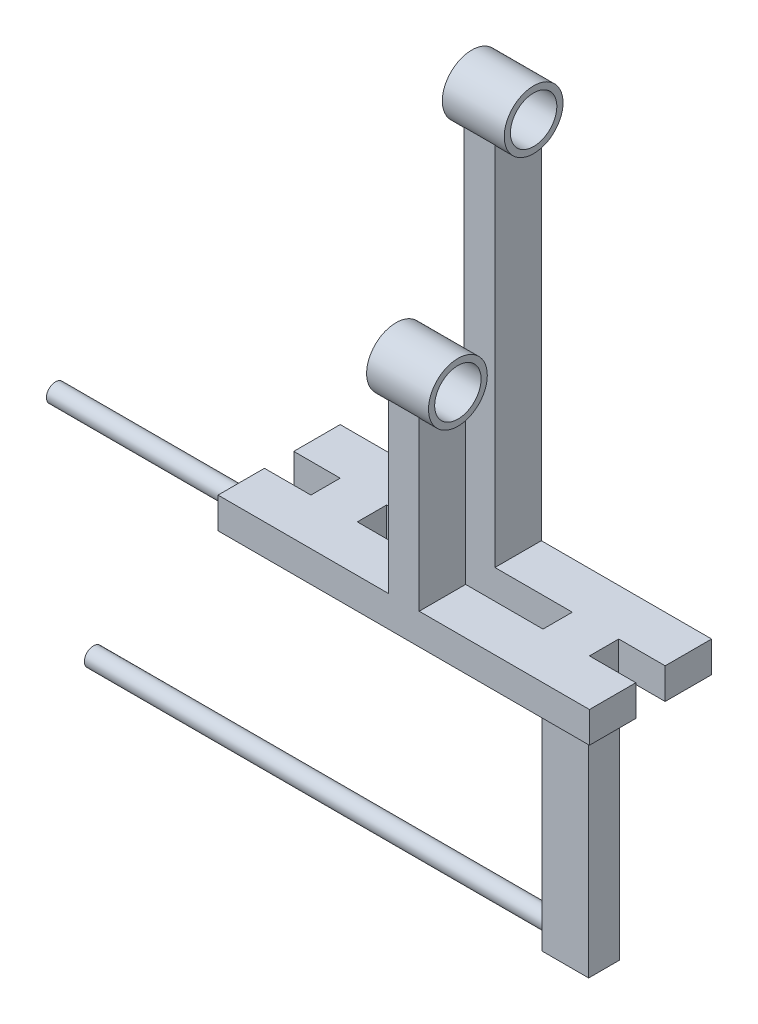
SolidWorks part; units mm, degrees
ref_plane "Front Plane" through (0, 0, 0) normal (0, 0, 1) x (1, 0, 0)
ref_plane "Top Plane" through (0, 0, 0) normal (0, 1, 0) x (1, 0, 0)
ref_plane "Right Plane" through (0, 0, 0) normal (1, 0, 0) x (0, 0, -1)
sketch "Sketch2" plane through (0, 0, 0) normal (0, 1, 0) x (1, 0, 0)
  line L33 (60, -15) -> (-60, -15)
  line L34 (-60, -15) -> (-60, 0)
  line L46 (-60, 0) -> (-45, 0)
  line L47 (-45, 0) -> (-45, 9.4666)
  line L48 (-45, 9.4666) -> (-60, 9.4666)
  line L49 (-60, 9.4666) -> (-60, 24.4666)
  line L50 (-60, 24.4666) -> (60, 24.4666)
  line L51 (60, 24.4666) -> (60, 9.4666)
  line L52 (60, 9.4666) -> (45, 9.4666)
  line L53 (45, 9.4666) -> (45, 0)
  line L54 (45, 0) -> (60, 0)
  line L55 (60, 0) -> (60, -15)
  line L57 (-30, 0) -> (30, 0)
  line L58 (-30, 0) -> (-30, 9.4666)
  line L59 (-30, 9.4666) -> (30, 9.4666)
  line L60 (30, 0) -> (30, 9.4666)
  point P21 (0, 0)
  dimension "D1" = 120
  dimension "D2" = 39.4666
  dimension "D3" = 15
  dimension "D4" = 60
  dimension "D5" = 15
  dimension "D6" = 15
extrude "Boss-Extrude2" add sketch "Sketch2" along normal blind 10
sketch "Sketch3" plane through (0, 10, 0) normal (0, 1, 0) x (1, 0, 0)
  line L0 (-30, 0) -> (30, 0) construction
  line L1 (-5, 0) -> (5, 0)
  line L2 (-5, 0) -> (-5, -15)
  line L3 (-5, -15) -> (5, -15)
  line L4 (5, 0) -> (5, -15)
  line L5 (-60, -15) -> (60, -15) construction
  line L6 (60, 24.4666) -> (-60, 24.4666) construction
  line L7 (-5, 24.4666) -> (5, 24.4666)
  line L8 (-5, 24.4666) -> (-5, 9.4666)
  line L9 (-5, 9.4666) -> (5, 9.4666)
  line L10 (5, 24.4666) -> (5, 9.4666)
  line L11 (30, 9.4666) -> (-30, 9.4666) construction
  dimension "D1" = 5
  dimension "D2" = 10
extrude "Boss-Extrude3" add sketch "Sketch3" along normal blind 60
sketch "Sketch4" plane through (0, 70, 0) normal (0, 1, 0) x (1, 0, 0)
  line L4 (-5, 24.4666) -> (-5, 9.4666)
  line L5 (-5, 9.4666) -> (5, 9.4666)
  line L6 (5, 9.4666) -> (5, 24.4666)
  line L7 (5, 24.4666) -> (-5, 24.4666)
  line L8 (-5, 24.4666) -> (-5, 9.4666)
  line L9 (-5, 9.4666) -> (5, 9.4666)
  line L10 (5, 9.4666) -> (5, 24.4666)
  line L11 (5, 24.4666) -> (-5, 24.4666)
  dimension "D1" = 0
extrude "Boss-Extrude4" add sketch "Sketch4" along normal blind 64.0503
sketch "Sketch6" plane through (0, 0, 0) normal (1, 0, 0) x (0, 0, -1)
  line L0 (-15, 70) -> (0, 70) construction
  line L1 (9.4666, 134.0503) -> (24.4666, 134.0503) construction
  line L2 (0, 70) -> (0, 10) construction
  line L3 (24.4666, 134.0503) -> (24.4666, 10) construction
  circle A0 centre (-7.5, 70) radius 7.5
  circle A1 centre (16.9666, 134.0503) radius 7.5
  dimension "D1" = 15
  dimension "D2" = 7.5
  dimension "D3" = 7.5
extrude "Extrude-Thin1" add sketch "Sketch6" along normal mid plane 20 thin
sketch "Sketch7" plane through (5, 0, 0) normal (1, 0, 0) x (0, 0, -1)
  line L1 (0, 70) -> (-15, 70)
  line L2 (0, 70) -> (-15, 70)
  line L3 (24.4666, 134.0503) -> (9.4666, 134.0503)
  line L4 (24.4666, 134.0503) -> (9.4666, 134.0503)
  arc A1 (-15, 70) -> (0, 70) centre (-7.5, 70) ccw
  arc A2 (-15, 70) -> (0, 70) centre (-7.5, 70) ccw
  arc A3 (9.4666, 134.0503) -> (24.4666, 134.0503) centre (16.9666, 134.0503) ccw
  arc A4 (9.4666, 134.0503) -> (24.4666, 134.0503) centre (16.9666, 134.0503) ccw
  dimension "D1" = 0
  dimension "D2" = 0
extrude "Cut-Extrude1" cut sketch "Sketch7" against normal through all both and the other way through all
sketch "Sketch8" plane through (0, 0, 0) normal (0, -1, 0) x (1, 0, 0)
  line L0 (30, 0) -> (30, -9.4666) construction
  line L1 (30, -9.75) -> (45, -9.75)
  line L2 (30, -9.75) -> (30, 0.25)
  line L3 (30, 0.25) -> (45, 0.25)
  line L4 (45, -9.75) -> (45, 0.25)
  line L5 (45, 0) -> (45, -9.4666) construction
  line L6 (-60, 15) -> (60, 15) construction
  dimension "D1" = 10
  dimension "D2" = 14.75
extrude "Boss-Extrude5" add sketch "Sketch8" along normal blind 80
sketch "Sketch9" plane through (30, 0, 0) normal (-1, 0, 0) x (0, 0, 1)
  line L0 (0.25, -80) -> (0.25, 0) construction
  line L1 (0.25, -80) -> (-9.75, -80) construction
  circle A0 centre (-4.75, -75) radius 2.95
  dimension "D1" = 5.9
  dimension "D2" = 5
  dimension "D3" = 5
extrude "Boss-Extrude6" add sketch "Sketch9" along normal blind 150
sketch "Sketch10" plane through (-60, 0, 0) normal (-1, 0, 0) x (0, 0, 1)
  line L0 (0, 10) -> (15, 10) construction
  line L1 (15, 10) -> (15, 0) construction
  circle A0 centre (7.5, 5) radius 2.95
  dimension "D1" = 5.9
  dimension "D2" = 5
  dimension "D3" = 7.5
extrude "Boss-Extrude7" add sketch "Sketch10" along normal blind 60
ref_plane "Plane1" through (0, 11.4078, 29.8742) normal (0, 0.3567, 0.9342) x (-1, 0, 0)
ref_plane "MatingPlane" through (0, 23.644, 61.9174) normal (0, 0.3567, 0.9342) x (-1, 0, 0)
